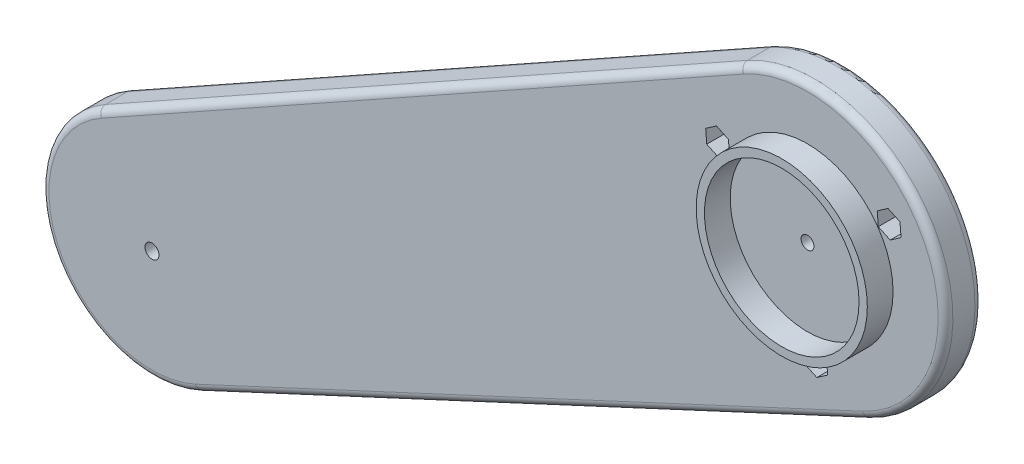
SolidWorks part; units mm, degrees
ref_plane "Front Plane" through (0, 0, 0) normal (0, 0, 1) x (1, 0, 0)
ref_plane "Top Plane" through (0, 0, 0) normal (0, 1, 0) x (1, 0, 0)
ref_plane "Right Plane" through (0, 0, 0) normal (1, 0, 0) x (0, 0, -1)
sketch "Sketch1" plane through (0, 0, 0) normal (0, 0, 1) x (1, 0, 0)
  line L0 (-192.7236, -64.8661) -> (-18.3113, 32.7253)
  line L1 (-165.4289, -118.2509) -> (15.8071, -34.0057)
  arc A2 (15.8071, -34.0057) -> (-18.3113, 32.7253) centre (0, 0) ccw
  arc A3 (-192.7236, -64.8661) -> (-165.4289, -118.2509) centre (-178.0746, -91.0463) ccw
  dimension "D1" = 75
  dimension "D2" = 60
  dimension "D3" = 200
extrude "Boss-Extrude1" add sketch "Sketch1" along normal blind 10
fillet "Fillet1" radius 2 8 edges at (-105.5174, -16.0704, 10) (33.389, 17.0712, 10) (-74.8109, -76.1283, 10) (-204.7858, -104.7033, 10) (-74.8109, -76.1283, 0) (33.389, 17.0712, 0) (-105.5174, -16.0704, 0) (-204.7858, -104.7033, 0)
sketch "Sketch3" plane through (0, 0, 10) normal (0, 0, 1) x (1, 0, 0)
  circle A0 centre (-178.0746, -91.0463) radius 1.9
  dimension "D1" = 3.8
extrude "Cut-Extrude3" cut sketch "Sketch3" against normal blind 240
sketch "Sketch4" plane through (0, 0, 10) normal (0, 0, 1) x (1, 0, 0)
  line L18 (0, 0) -> (22.1781, 15.3991)
  line L19 (1.9491, -23.3388) -> (-0.9916, -25.3806)
  line L20 (19.2374, 13.3573) -> (22.476, 11.8315)
  line L21 (22.476, 11.8315) -> (25.4167, 13.8733)
  line L22 (25.4167, 13.8733) -> (25.1187, 17.4409)
  line L23 (25.1187, 17.4409) -> (21.8801, 18.9667)
  line L24 (21.8801, 18.9667) -> (18.9395, 16.9249)
  line L25 (18.9395, 16.9249) -> (19.2374, 13.3573)
  line L26 (-0.9916, -25.3806) -> (-0.6937, -28.9481)
  line L27 (-0.6937, -28.9481) -> (2.5449, -30.4739)
  line L28 (2.5449, -30.4739) -> (5.4856, -28.4321)
  line L29 (5.4856, -28.4321) -> (5.1876, -24.8645)
  line L30 (5.1876, -24.8645) -> (1.9491, -23.3388)
  line L31 (-21.1865, 9.9815) -> (-21.4844, 13.549)
  line L32 (-21.4844, 13.549) -> (-24.723, 15.0748)
  line L33 (-24.723, 15.0748) -> (-27.6636, 13.033)
  line L34 (-27.6636, 13.033) -> (-27.3657, 9.4654)
  line L35 (-27.3657, 9.4654) -> (-24.1271, 7.9396)
  line L36 (-24.1271, 7.9396) -> (-21.1865, 9.9815)
  circle A2 centre (22.1781, 15.3991) radius 3.1004 construction
  point P22 (0, 0)
  point P26 (0, 0)
  dimension "D1" = 3.58
  dimension "D2" = 27
  dimension "D3" = 3
extrude "Cut-Extrude4" cut sketch "Sketch4" against normal blind 5
sketch "Sketch6" plane through (0, 0, 10) normal (0, 0, 1) x (1, 0, 0)
  circle A0 centre (2.247, -26.9063) radius 1.75
  circle A1 centre (-24.4251, 11.5072) radius 1.75
  circle A2 centre (22.1781, 15.3991) radius 1.75
  point P14 (0, 0)
  dimension "D1" = 3.5
  dimension "D2" = 3
extrude "Cut-Extrude8" cut sketch "Sketch6" against normal blind 10 contours A2 | A0 | A1
sketch "Sketch7" plane through (0, 0, 10) normal (0, 0, 1) x (1, 0, 0)
  circle A0 centre (0, 0) radius 23.25
  circle A1 centre (0, 0) radius 21
  dimension "D1" = 46.5
  dimension "D2" = 42
extrude "Boss-Extrude2" add sketch "Sketch7" along normal blind 7
sketch "Sketch8" plane through (0, 0, 0) normal (0, 0, -1) x (-1, 0, 0)
  line L7 (181.2622, -92.676) -> (181.0797, -89.1007)
  line L8 (181.0797, -89.1007) -> (177.8922, -87.471)
  line L9 (177.8922, -87.471) -> (174.8871, -89.4166)
  line L10 (174.8871, -89.4166) -> (175.0695, -92.992)
  line L11 (175.0695, -92.992) -> (178.257, -94.6217)
  line L12 (178.257, -94.6217) -> (181.2622, -92.676)
  circle A2 centre (178.0746, -91.0463) radius 3.1004 construction
  dimension "D1" = 3.58
extrude "Cut-Extrude9" cut sketch "Sketch8" against normal blind 5
sketch "Sketch9" plane through (0, 0, 10) normal (0, 0, 1) x (1, 0, 0)
  circle A0 centre (0, 0) radius 1.75
  dimension "D1" = 3.5
extrude "Cut-Extrude10" cut sketch "Sketch9" against normal blind 10
